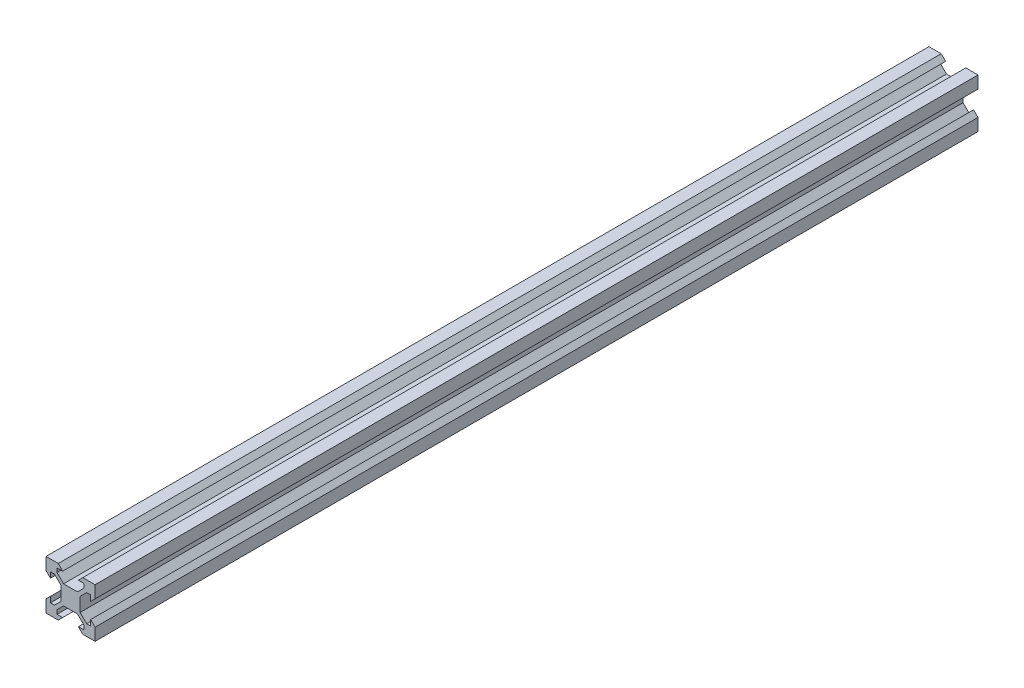
SolidWorks part; units mm, degrees
ref_plane "Front Plane" through (0, 0, 0) normal (0, 0, 1) x (1, 0, 0)
ref_plane "Top Plane" through (0, 0, 0) normal (0, 1, 0) x (1, 0, 0)
ref_plane "Right Plane" through (0, 0, 0) normal (1, 0, 0) x (0, 0, -1)
sketch "Sketch1" plane through (0, 0, 0) normal (0, 0, 1) x (1, 0, 0)
  line L0 (-10, 10) -> (-10, 5)
  line L1 (-10, 5) -> (-8.2, 3.2)
  line L2 (-8.2, 3.2) -> (-8.2, 5.4993)
  line L3 (-8.2, 5.4993) -> (-6.56, 5.4993)
  line L4 (-6.56, 5.4993) -> (-3.9007, 2.84)
  line L5 (-3.9007, 2.84) -> (-3.9007, -2.84)
  line L6 (-3.9007, -2.84) -> (-6.56, -5.4993)
  line L7 (-6.56, -5.4993) -> (-8.2, -5.4993)
  line L8 (-8.2, -5.4993) -> (-8.2, -3.2)
  line L9 (-8.2, -3.2) -> (-10, -5)
  line L10 (-10, -5) -> (-10, -10)
  line L11 (-10, -10) -> (-5, -10)
  line L12 (-5, -10) -> (-3.2, -8.2)
  line L13 (-3.2, -8.2) -> (-5.4993, -8.2)
  line L14 (-5.4993, -8.2) -> (-5.4993, -6.56)
  line L15 (-5.4993, -6.56) -> (-2.84, -3.9007)
  line L16 (-2.84, -3.9007) -> (2.84, -3.9007)
  line L17 (2.84, -3.9007) -> (5.4993, -6.56)
  line L18 (5.4993, -6.56) -> (5.4993, -8.2)
  line L19 (5.4993, -8.2) -> (3.2, -8.2)
  line L20 (3.2, -8.2) -> (5, -10)
  line L21 (5, -10) -> (10, -10)
  line L22 (10, -10) -> (10, -5)
  line L23 (10, -5) -> (8.2, -3.2)
  line L24 (8.2, -3.2) -> (8.2, -5.4993)
  line L25 (8.2, -5.4993) -> (6.56, -5.4993)
  line L26 (6.56, -5.4993) -> (3.9007, -2.84)
  line L27 (3.9007, -2.84) -> (3.9007, 2.84)
  line L28 (3.9007, 2.84) -> (6.56, 5.4993)
  line L29 (6.56, 5.4993) -> (8.2, 5.4993)
  line L30 (8.2, 5.4993) -> (8.2, 3.2)
  line L31 (8.2, 3.2) -> (10, 5)
  line L32 (10, 5) -> (10, 10)
  line L33 (10, 10) -> (5, 10)
  line L34 (5, 10) -> (3.2, 8.2)
  line L35 (3.2, 8.2) -> (5.4993, 8.2)
  line L36 (5.4993, 8.2) -> (5.4993, 6.56)
  line L37 (5.4993, 6.56) -> (2.84, 3.9007)
  line L38 (2.84, 3.9007) -> (-2.84, 3.9007)
  line L39 (-2.84, 3.9007) -> (-5.4993, 6.56)
  line L40 (-5.4993, 6.56) -> (-5.4993, 8.2)
  line L41 (-5.4993, 8.2) -> (-3.2, 8.2)
  line L42 (-3.2, 8.2) -> (-5, 10)
  line L43 (-5, 10) -> (-10, 10)
  circle A0 centre (0, 0) radius 2.1
extrude "Boss-Extrude1" add sketch "Sketch1" against normal blind 340
ref_plane "基准面1" through (0, 0, 0) normal (0, 0, 1) x (1, 0, 0)
sketch "草图1" plane through (0, 0, 0) normal (0, 0, 1) x (1, 0, 0)
  line L44 (-5, 10) -> (-10, 10)
  line L45 (-10, 10) -> (-10, 5)
  line L46 (-10, 5) -> (-8.2, 3.2)
  line L47 (-8.2, 3.2) -> (-8.2, 5.4993)
  line L48 (-8.2, 5.4993) -> (-6.56, 5.4993)
  line L49 (-6.56, 5.4993) -> (-3.9007, 2.84)
  line L50 (-3.9007, 2.84) -> (-3.9007, -2.84)
  line L51 (-3.9007, -2.84) -> (-6.56, -5.4993)
  line L52 (-6.56, -5.4993) -> (-8.2, -5.4993)
  line L53 (-8.2, -5.4993) -> (-8.2, -3.2)
  line L54 (-8.2, -3.2) -> (-10, -5)
  line L55 (-10, -5) -> (-10, -10)
  line L56 (-10, -10) -> (-5, -10)
  line L57 (-5, -10) -> (-3.2, -8.2)
  line L58 (-3.2, -8.2) -> (-5.4993, -8.2)
  line L59 (-5.4993, -8.2) -> (-5.4993, -6.56)
  line L60 (-5.4993, -6.56) -> (-2.84, -3.9007)
  line L61 (-2.84, -3.9007) -> (2.84, -3.9007)
  line L62 (2.84, -3.9007) -> (5.4993, -6.56)
  line L63 (5.4993, -6.56) -> (5.4993, -8.2)
  line L64 (5.4993, -8.2) -> (3.2, -8.2)
  line L65 (3.2, -8.2) -> (5, -10)
  line L66 (5, -10) -> (10, -10)
  line L67 (10, -10) -> (10, -5)
  line L68 (10, -5) -> (8.2, -3.2)
  line L69 (8.2, -3.2) -> (8.2, -5.4993)
  line L70 (8.2, -5.4993) -> (6.56, -5.4993)
  line L71 (6.56, -5.4993) -> (3.9007, -2.84)
  line L72 (3.9007, -2.84) -> (3.9007, 2.84)
  line L73 (3.9007, 2.84) -> (6.56, 5.4993)
  line L74 (6.56, 5.4993) -> (8.2, 5.4993)
  line L75 (8.2, 5.4993) -> (8.2, 3.2)
  line L76 (8.2, 3.2) -> (10, 5)
  line L77 (10, 5) -> (10, 10)
  line L78 (10, 10) -> (5, 10)
  line L79 (5, 10) -> (3.2, 8.2)
  line L80 (3.2, 8.2) -> (5.4993, 8.2)
  line L81 (5.4993, 8.2) -> (5.4993, 6.56)
  line L82 (5.4993, 6.56) -> (2.84, 3.9007)
  line L83 (2.84, 3.9007) -> (-2.84, 3.9007)
  line L84 (-2.84, 3.9007) -> (-5.4993, 6.56)
  line L85 (-5.4993, 6.56) -> (-5.4993, 8.2)
  line L86 (-5.4993, 8.2) -> (-3.2, 8.2)
  line L87 (-3.2, 8.2) -> (-5, 10)
  line L88 (-5, 10) -> (-10, 10)
  line L89 (-10, 10) -> (-10, 5)
  line L90 (-10, 5) -> (-8.2, 3.2)
  line L91 (-8.2, 3.2) -> (-8.2, 5.4993)
  line L92 (-8.2, 5.4993) -> (-6.56, 5.4993)
  line L93 (-6.56, 5.4993) -> (-3.9007, 2.84)
  line L94 (-3.9007, 2.84) -> (-3.9007, -2.84)
  line L95 (-3.9007, -2.84) -> (-6.56, -5.4993)
  line L96 (-6.56, -5.4993) -> (-8.2, -5.4993)
  line L97 (-8.2, -5.4993) -> (-8.2, -3.2)
  line L98 (-8.2, -3.2) -> (-10, -5)
  line L99 (-10, -5) -> (-10, -10)
  line L100 (-10, -10) -> (-5, -10)
  line L101 (-5, -10) -> (-3.2, -8.2)
  line L102 (-3.2, -8.2) -> (-5.4993, -8.2)
  line L103 (-5.4993, -8.2) -> (-5.4993, -6.56)
  line L104 (-5.4993, -6.56) -> (-2.84, -3.9007)
  line L105 (-2.84, -3.9007) -> (2.84, -3.9007)
  line L106 (2.84, -3.9007) -> (5.4993, -6.56)
  line L107 (5.4993, -6.56) -> (5.4993, -8.2)
  line L108 (5.4993, -8.2) -> (3.2, -8.2)
  line L109 (3.2, -8.2) -> (5, -10)
  line L110 (5, -10) -> (10, -10)
  line L111 (10, -10) -> (10, -5)
  line L112 (10, -5) -> (8.2, -3.2)
  line L113 (8.2, -3.2) -> (8.2, -5.4993)
  line L114 (8.2, -5.4993) -> (6.56, -5.4993)
  line L115 (6.56, -5.4993) -> (3.9007, -2.84)
  line L116 (3.9007, -2.84) -> (3.9007, 2.84)
  line L117 (3.9007, 2.84) -> (6.56, 5.4993)
  line L118 (6.56, 5.4993) -> (8.2, 5.4993)
  line L119 (8.2, 5.4993) -> (8.2, 3.2)
  line L120 (8.2, 3.2) -> (10, 5)
  line L121 (10, 5) -> (10, 10)
  line L122 (10, 10) -> (5, 10)
  line L123 (5, 10) -> (3.2, 8.2)
  line L124 (3.2, 8.2) -> (5.4993, 8.2)
  line L125 (5.4993, 8.2) -> (5.4993, 6.56)
  line L126 (5.4993, 6.56) -> (2.84, 3.9007)
  line L127 (2.84, 3.9007) -> (-2.84, 3.9007)
  line L128 (-2.84, 3.9007) -> (-5.4993, 6.56)
  line L129 (-5.4993, 6.56) -> (-5.4993, 8.2)
  line L130 (-5.4993, 8.2) -> (-3.2, 8.2)
  line L131 (-3.2, 8.2) -> (-5, 10)
  dimension "D1" = 0
extrude "凸台-拉伸1" add sketch "草图1" along normal blind 20
